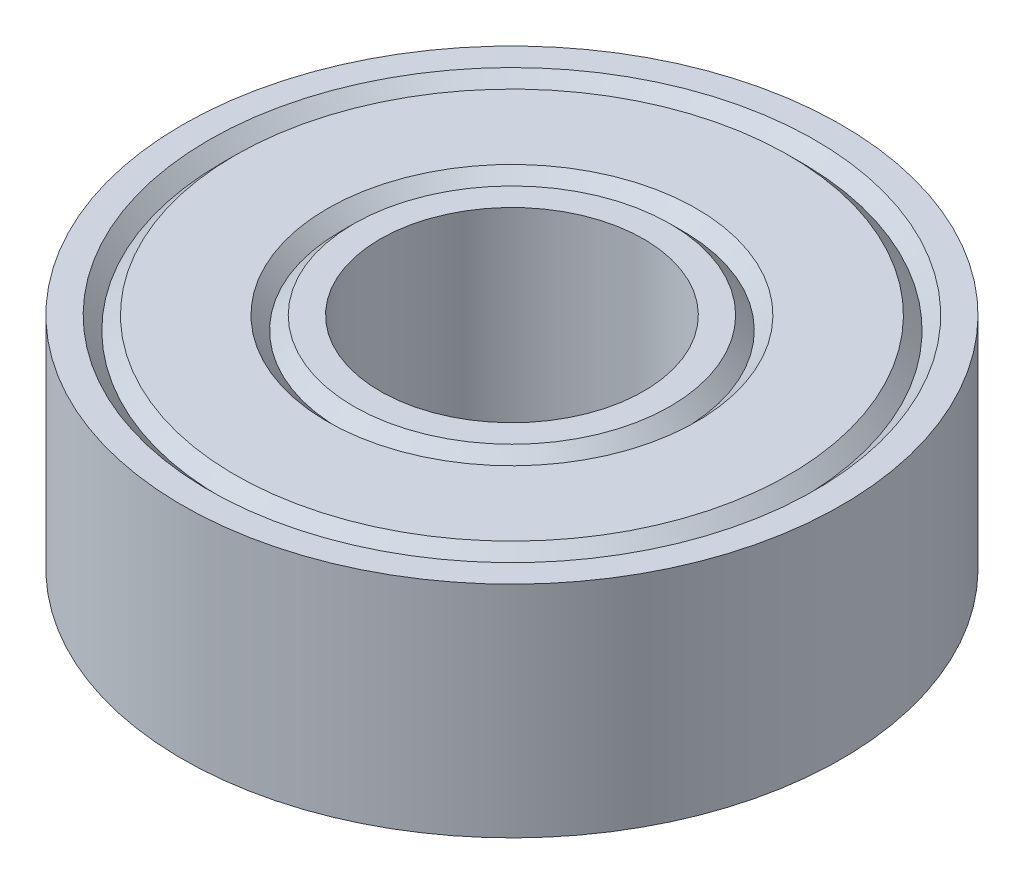
SolidWorks part; units mm, degrees
ref_plane "Front Plane" through (0, 0, 0) normal (0, 0, 1) x (1, 0, 0)
ref_plane "Top Plane" through (0, 0, 0) normal (0, 1, 0) x (1, 0, 0)
ref_plane "Right Plane" through (0, 0, 0) normal (1, 0, 0) x (0, 0, -1)
sketch "Sketch1" plane through (0, 0, 0) normal (0, 0, 1) x (1, 0, 0)
  line L0 (0, 2.5) -> (0, -2.5) construction
  line L1 (-3, 2.5) -> (-3.6, 2.5)
  line L2 (-3, 2.5) -> (-3, -2.5)
  line L3 (-3, -2.5) -> (-3.6, -2.5)
  line L4 (-7.5, 2.5) -> (-7.5, -2.5)
  line L5 (-6.9, 2.5) -> (-6.6, 2.2)
  line L6 (-6.6, 2.2) -> (-6.3, 2.5)
  line L7 (-4.2, 2.5) -> (-3.9, 2.2)
  line L8 (-3.9, 2.2) -> (-3.6, 2.5)
  line L9 (-6.9, -2.5) -> (-6.6, -2.2)
  line L10 (-6.6, -2.2) -> (-6.3, -2.5)
  line L11 (-4.2, -2.5) -> (-3.9, -2.2)
  line L12 (-3.9, -2.2) -> (-3.6, -2.5)
  line L13 (-4.2, -2.5) -> (-6.3, -2.5)
  line L14 (-6.9, -2.5) -> (-7.5, -2.5)
  line L15 (-6.9, 2.5) -> (-7.5, 2.5)
  line L16 (-4.2, 2.5) -> (-6.3, 2.5)
  line L17 (-6.6, 2.2) -> (-3.9, 2.2) construction
  line L18 (-6.6, 2.2) -> (-6.6, -2.2) construction
  line L19 (-3.9, -2.2) -> (-6.6, -2.2) construction
  line L20 (-3.9, 2.2) -> (-3.9, -2.2) construction
  line L21 (-6.6, 0) -> (-5.7, 0) construction
  line L22 (-3.6, 2.5) -> (-4.2, 2.5) construction
  line L23 (-5.7, 0) -> (-4.8, 0) construction
  line L24 (-6.6, 0) -> (-7.5, 0) construction
  line L25 (-4.8, 0) -> (-3.9, 0) construction
  line L26 (-3.9, 0) -> (-3, 0) construction
  dimension "D1" = 5
  dimension "D2" = 6
  dimension "D3" = 15
revolve "Revolve1" add sketch "Sketch1" angle 360 about L0
